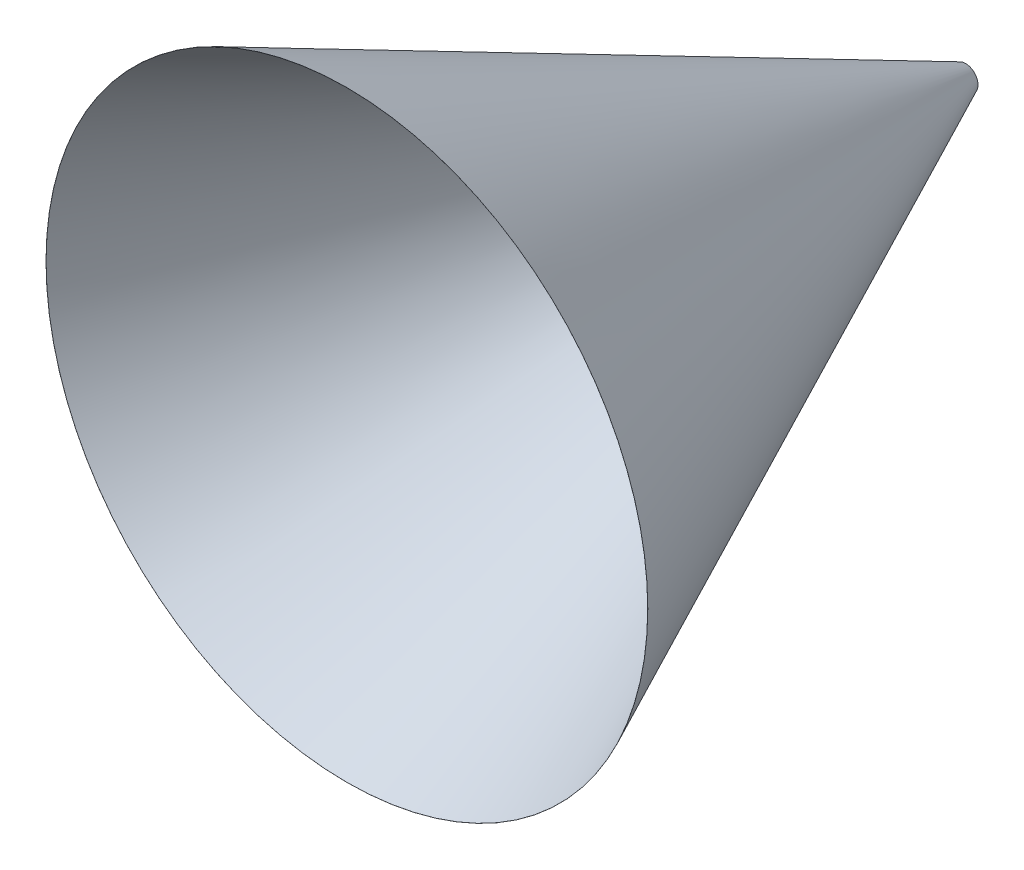
SolidWorks part; units mm, degrees
ref_plane "前视基准面" through (0, 0, 0) normal (0, 0, 1) x (1, 0, 0)
ref_plane "上视基准面" through (0, 0, 0) normal (0, 1, 0) x (1, 0, 0)
ref_plane "右视基准面" through (0, 0, 0) normal (1, 0, 0) x (0, 0, -1)
sketch "草图1" plane through (0, 0, 0) normal (0, 0, 1) x (1, 0, 0)
  circle A0 centre (0, 0) radius 3
  dimension "D1" = 6
extrude "凸台-拉伸1" add sketch "草图1" along normal blind 150 draft 25 draft outward yes
shell "抽壳1" thickness 0.01
